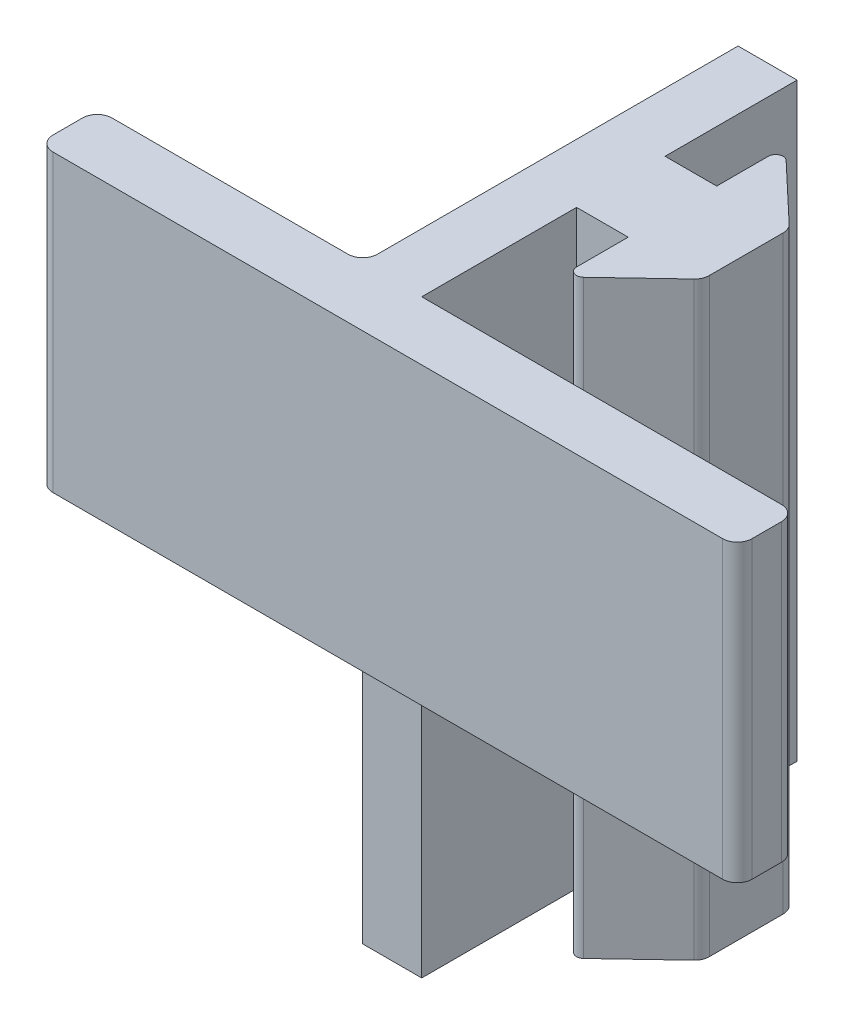
SolidWorks part; units mm, degrees
ref_plane "Front Plane" through (0, 0, 0) normal (0, 0, 1) x (1, 0, 0)
ref_plane "Top Plane" through (0, 0, 0) normal (0, 1, 0) x (1, 0, 0)
ref_plane "Right Plane" through (0, 0, 0) normal (1, 0, 0) x (0, 0, -1)
sketch "Sketch1" plane through (0, 0, 0) normal (0, 1, 0) x (1, 0, 0)
  line L0 (6.5, 11.1595) -> (6.5, 7.6595)
  line L1 (3, 0.6595) -> (28.4, 0.6595)
  line L3 (-4.9999, -3.3405) -> (28.4, -3.3405)
  line L4 (28.4, 0.6595) -> (28.4, -3.3405)
  line L6 (-1, 0.6595) -> (-1, 26.1095)
  line L7 (-1, 26.1095) -> (3, 26.1095)
  line L8 (3, 0.6595) -> (3, 11.1595)
  line L9 (3, 17.1595) -> (6.5, 17.1595)
  line L11 (3, 11.1595) -> (6.5, 11.1595)
  line L14 (6.5, 20.6595) -> (6.5, 17.1595)
  line L19 (3, 17.1595) -> (3, 26.1095)
  line L21 (7.3436, 21.0227) -> (11.1873, 17.3859)
  line L25 (11.5, 16.6595) -> (11.5, 11.6595)
  line L26 (7.3436, 7.2964) -> (11.1873, 10.9332)
  line L27 (6.5, 17.1595) -> (6.5, 11.1595) construction
  line L28 (6.5, 14.1595) -> (-1, 14.1595) construction
  line L29 (-1, 0.6595) -> (-19, 0.6595)
  line L31 (-4.9999, -3.3405) -> (-19, -3.3405)
  line L32 (-19, 0.6595) -> (-19, -3.3405)
  arc A0 (7.3436, 21.0227) -> (6.5, 20.6595) centre (7, 20.6595) ccw
  arc A1 (6.5, 7.6595) -> (7.3436, 7.2964) centre (7, 7.6595) ccw
  arc A2 (11.1873, 17.3859) -> (11.5, 16.6595) centre (10.5, 16.6595) cw
  arc A3 (11.1873, 10.9332) -> (11.5, 11.6595) centre (10.5, 11.6595) ccw
  point P0 (4.75, 11.1595)
  point P24 (11.5, 17.09)
  dimension "D6" = 0.5
  dimension "D8" = 1
  dimension "D1" = 25.45
  dimension "D2" = 6
  dimension "D3" = 5
  dimension "D4" = 4
  dimension "D5" = 3.5
  dimension "D7" = 5
  dimension "D9" = 25.4
  dimension "D10" = 18
  dimension "D11" = 4
  dimension "D12" = 10.5
  dimension "D13" = 4
  dimension "D14" = 2.5
  dimension "D15" = 3.5
  dimension "D16" = 3.5
extrude "Main-Extrude" add sketch "Sketch1" along normal blind 40
sketch "Sketch4" plane through (0, 0, 3.3405) normal (0, 0, 1) x (1, 0, 0)
  line L0 (28.4, 40) -> (28.4, 0) construction
  line L1 (-19, 40) -> (28.4, 40)
  line L2 (-19, 40) -> (-19, 20)
  line L3 (-19, 20) -> (28.4, 20)
  line L4 (28.4, 40) -> (28.4, 20)
  dimension "D1" = 20
fillet "Fillet1" radius 1 3 edges at (-19, 20, 3.3405) (28.4, 20, -0.6595) (28.4, 20, 3.3405)
fillet "Fillet2" radius 1 1 edges at (-19, 20, -0.6595)
fillet "Fillet3" radius 1 1 edges at (-1, 20, -0.6595)
sketch "Sketch5" plane through (0, 0, 0) normal (0, -1, 0) x (1, 0, 0)
  line L0 (-19, 1.0984) -> (-19, -0.6595) construction
  line L1 (-19, 0.3405) -> (-19, 2.3405) construction
  line L2 (-16.1153, -0.6595) -> (-19, -0.6595) construction
  line L3 (-2, -0.6595) -> (-18, -0.6595) construction
  line L4 (25.2413, 3.3405) -> (28.4, 3.3405) construction
  line L5 (-18, 3.3405) -> (27.4, 3.3405) construction
  line L6 (28.4, 1.3405) -> (28.4, 3.3405) construction
  line L7 (28.4, 2.3405) -> (28.4, 0.3405) construction
  line L8 (-1, -26.1095) -> (-1, -1.6595) construction
  line L9 (-19, -0.6595) -> (-4.5184, -0.6595)
  line L10 (-19, -0.6595) -> (-19, 3.3405)
  line L11 (-19, 3.3405) -> (28.4, 3.3405)
  line L12 (28.4, -0.6595) -> (28.4, 3.3405)
  line L14 (-4.5184, -0.6595) -> (-4.5184, -5.5165)
  line L15 (-4.5184, -5.5165) -> (-1, -5.5165)
  line L16 (-1, -0.6595) -> (-1, -5.5165)
  line L17 (3, -0.6595) -> (3, -11.1595) construction
  line L19 (6.5946, -0.6595) -> (6.5946, -5.5165)
  line L20 (6.5946, -5.5165) -> (3, -5.5165)
  line L21 (3, -0.6595) -> (3, -5.5165)
  line L22 (-1, -0.6595) -> (3, -0.6595)
  line L23 (6.5946, -0.6595) -> (28.4, -0.6595)
extrude "Cut-Extrude1" cut sketch "Sketch5" against normal blind 20
